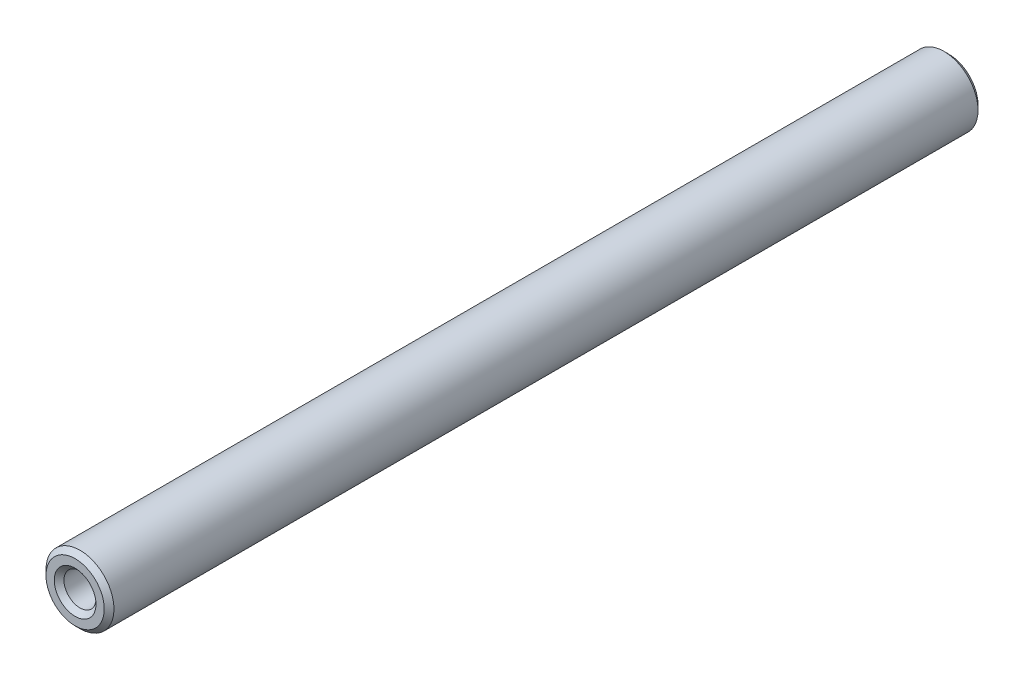
SolidWorks part; units mm, degrees
material "7075-T6, Plate (SS)"
ref_plane "前视基准面" through (0, 0, 0) normal (0, 0, 1) x (1, 0, 0)
ref_plane "上视基准面" through (0, 0, 0) normal (0, 1, 0) x (1, 0, 0)
ref_plane "右视基准面" through (0, 0, 0) normal (1, 0, 0) x (0, 0, -1)
sketch "草图1" plane through (0, 0, 0) normal (0, 0, 1) x (1, 0, 0)
  circle A0 centre (0, 0) radius 3.5
  dimension "D1" = 7
extrude "拉伸1" add sketch "草图1" along normal mid plane 90
hole_wizard "M4 螺纹孔1" positions "3D草图1" profile "草图2" tap size "M4" standard "GB"
sketch3d "3D草图1"
  line L0 (0, 0, 45) -> (0, 0, -45) construction
  circle A0 centre (0, 0, 45) radius 3.5 construction
  point P0 (0, 0, 45)
  point P2 (0, 0, -45)
  point P10 (0, 0, 48.5)
sketch "草图2" plane through (0, 0, 45) normal (1, 0, 0) x (0, -1, 0)
  line L0 (0, 0) -> (0, 13.0914)
  line L1 (0, 13.0914) -> (1.65, 12.1)
  line L2 (1.65, 12.1) -> (1.65, 0)
  line L5 (1.65, 0) -> (0, 0)
  line L10 (0, 13.0914) -> (-1.65, 12.1) construction
  line L11 (0, -6.35) -> (0, 107.95) construction
  dimension "螺纹孔钻头直径" = 3.3
  dimension "螺纹孔钻头深度" = 12.1
  dimension "导头角度" = 118
cosmetic thread "孔螺蚊线1" parameters "D1"=10, "D2"=4
cosmetic thread "孔螺蚊线2" parameters "D1"=10, "D2"=4
chamfer "倒角1" distance 0.5 angle 45 4 edges at (3.5, 0, -45) (-1.65, 0, -45) (3.5, 0, 45) (1.65, 0, 45)
